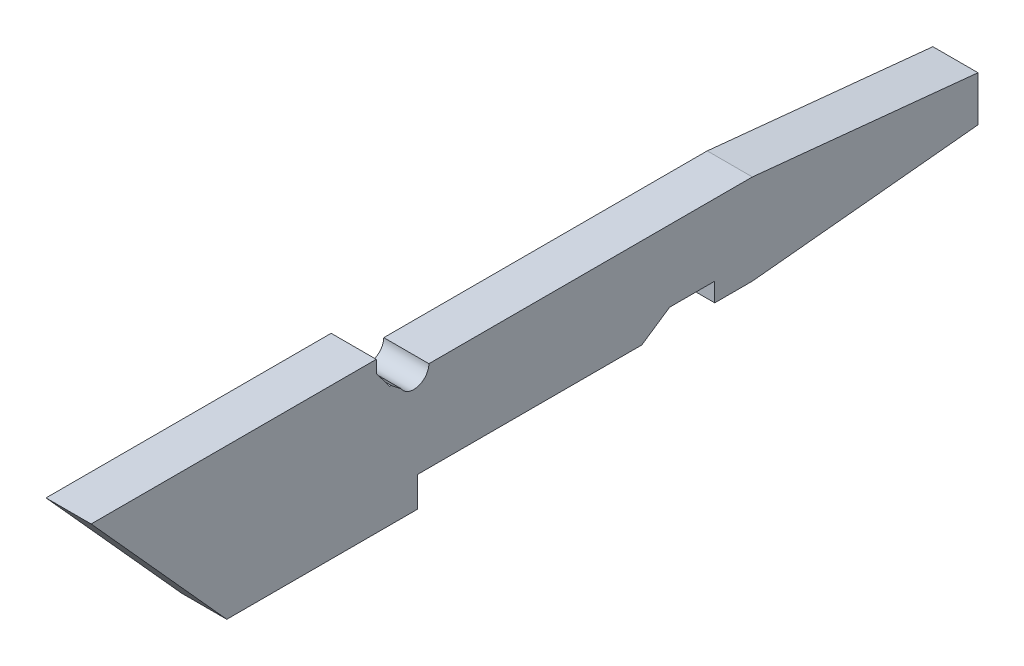
SolidWorks part; units mm, degrees
ref_plane "정면" through (0, 0, 0) normal (0, 0, 1) x (1, 0, 0)
ref_plane "윗면" through (0, 0, 0) normal (0, 1, 0) x (1, 0, 0)
ref_plane "우측면" through (0, 0, 0) normal (1, 0, 0) x (0, 0, -1)
sketch "스케치1" plane through (0, 0, 0) normal (1, 0, 0) x (0, 0, -1)
  line L0 (0, 6) -> (0, -6)
  line L1 (0, 6) -> (-60, 12)
  line L2 (-60, 12) -> (-146.0005, 12)
  line L3 (0, 0) -> (-217.778, 0) construction
  line L4 (0, -6) -> (-60, -12)
  line L5 (-60, -12) -> (-70, -12)
  line L6 (-70, -12) -> (-70, -7)
  line L7 (-70, -7) -> (-82, -7)
  line L8 (-82, -7) -> (-89.4031, -12)
  line L9 (-89.4031, -12) -> (-149, -12)
  line L10 (-156.0193, 12) -> (-146.0005, 12) construction
  line L11 (-156.0193, 12) -> (-156.4375, 12)
  line L12 (-160, 16.75) -> (-160, 20)
  line L13 (-160, 20) -> (-235.8163, 20)
  line L14 (-235.8163, 20) -> (-199.7397, -20)
  line L15 (-199.7397, -20) -> (-149, -20)
  line L16 (-149, -20) -> (-149, -12)
  line L17 (-153.3755, 9.9195) -> (-156.0193, 12)
  line L20 (-156.4375, 12) -> (-160, 16.75)
  arc A0 (-146.0005, 12) -> (-153.3755, 9.9195) centre (-150, 12.0656) cw
  dimension "D6" = 4
  dimension "D1" = 12
  dimension "D2" = 10
  dimension "D3" = 5
  dimension "D4" = 12
  dimension "D5" = 24
  dimension "D7" = 60
  dimension "D8" = 40
  dimension "D9" = 20
  dimension "D10" = 160
  dimension "D11" = 150
  dimension "D12" = 149
extrude "보스-돌출1" add sketch "스케치1" along normal mid plane 12
